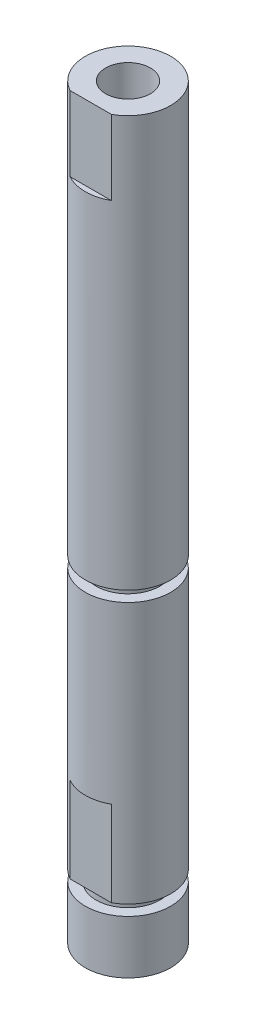
SolidWorks part; units mm, degrees
material "6061-T6 (SS)"
ref_plane "Alzado" through (0, 0, 0) normal (0, 0, 1) x (1, 0, 0)
ref_plane "Planta" through (0, 0, 0) normal (0, 1, 0) x (1, 0, 0)
ref_plane "Vista lateral" through (0, 0, 0) normal (1, 0, 0) x (0, 0, -1)
sketch "Croquis1" plane through (0, 0, 0) normal (0, 0, 1) x (1, 0, 0)
  line L0 (0, -35) -> (0, 35) construction
  line L1 (0, 35) -> (4, 35)
  line L2 (4, 35) -> (4, -3.52)
  line L3 (4, -3.52) -> (3, -3.52)
  line L4 (3, -3.52) -> (3, -4.52)
  line L5 (3, -4.52) -> (4, -4.52)
  line L6 (4, -4.52) -> (4, -29)
  line L7 (4, -29) -> (3, -29)
  line L8 (3, -29) -> (3, -30)
  line L9 (3, -30) -> (4, -30)
  line L10 (4, -30) -> (4, -35)
  line L11 (4, -35) -> (0, -35)
  line L12 (0, -35) -> (0, 35)
  point P2 (0, 0)
  dimension "D1" = 70
  dimension "D2" = 8
  dimension "D3" = 1
  dimension "D4" = 5
  dimension "D5" = 6
  dimension "D6" = 31.48
revolve "Revolución1" add sketch "Croquis1" angle 360 about L0
sketch "Croquis2" plane through (0, 0, 0) normal (1, 0, 0) x (0, 0, -1)
  line L0 (-4, -21) -> (-3.5, -21)
  line L1 (-4, -4.52) -> (-4, -29) construction
  line L2 (-3.5, -21) -> (-3.5, -29)
  line L3 (-3.5, -29) -> (-4, -29)
  line L4 (-4, -21) -> (-4, -29)
  line L6 (-4, -29) -> (4, -29) construction
  line L7 (-4, -35) -> (4, -35) construction
  line L8 (-4, 35) -> (-3.5, 35)
  line L9 (-4, 35) -> (-4, 28)
  line L10 (-4, 28) -> (-3.5, 28)
  line L11 (-3.5, 35) -> (-3.5, 28)
  dimension "D1" = 0.5
  dimension "D2" = 14
  dimension "D3" = 7
extrude "Cortar-Extruir1" cut sketch "Croquis2" against normal through all both and the other way through all
hole_wizard "Taladro roscado M5x0.81" positions "Croquis3" profile "Croquis4" tap size "M5x0.8" standard "Ansi Metric"
sketch "Croquis3" plane through (0, 35, 0) normal (0, 1, 0) x (1, 0, 0)
  point P0 (0, 0)
sketch "Croquis4" plane through (0, 35, 0) normal (1, 0, 0) x (0, 0, 1)
  line L0 (0, 0) -> (0, 9.2618)
  line L1 (0, 9.2618) -> (2.1, 8)
  line L2 (2.1, 8) -> (2.1, 0)
  line L5 (2.1, 0) -> (0, 0)
  line L10 (0, 9.2618) -> (-2.1, 8) construction
  line L11 (0, -6.35) -> (0, 107.95) construction
  dimension "Diámetro de perforador para roscar" = 4.2
  dimension "Profundidad de perforador para roscar" = 8
  dimension "Ángulo de perforador" = 118
cosmetic thread "Rosca de taladro1" parameters "D1"=10, "D2"=5
